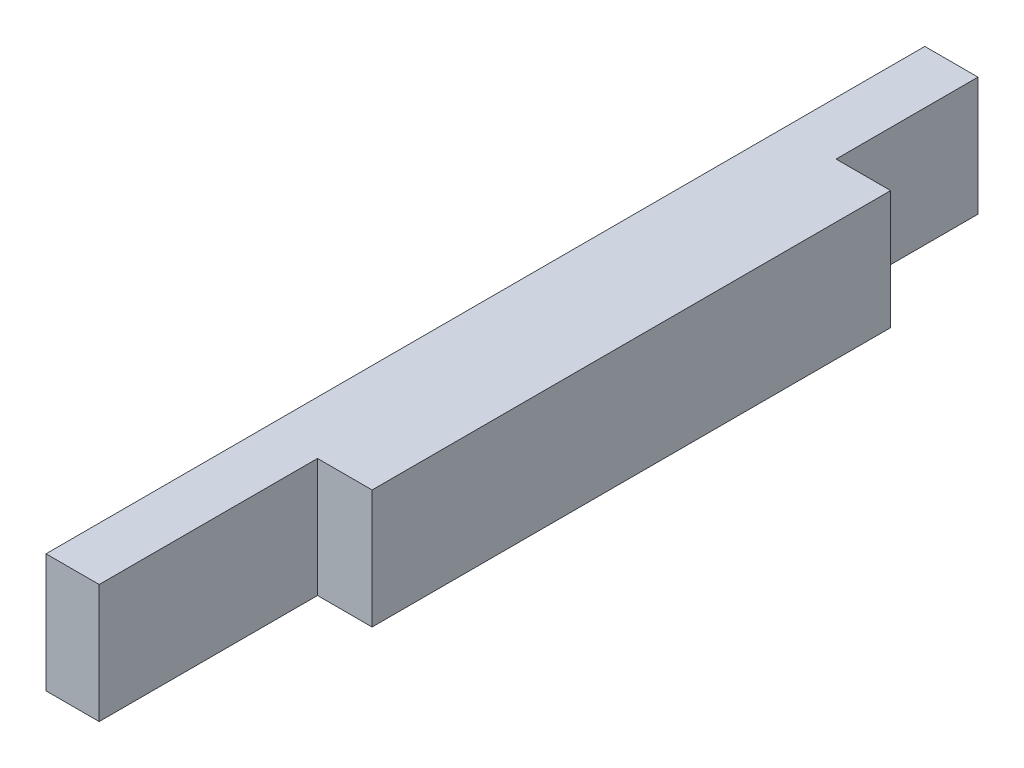
SolidWorks part; units mm, degrees
material "ABS"
ref_plane "Front Plane" through (0, 0, 0) normal (0, 0, 1) x (1, 0, 0)
ref_plane "Top Plane" through (0, 0, 0) normal (0, 1, 0) x (1, 0, 0)
ref_plane "Right Plane" through (0, 0, 0) normal (1, 0, 0) x (0, 0, -1)
sketch "Sketch2" plane through (0, 0, 0) normal (0, 1, 0) x (1, 0, 0)
  line L1 (0, 0) -> (4.95, 0)
  line L2 (0, 0) -> (0, 81.79)
  line L3 (0, 81.79) -> (4.95, 81.79)
  line L4 (10.03, 20.32) -> (10.03, 68.58)
  line L9 (10.03, 68.58) -> (4.95, 68.58)
  line L10 (4.95, 81.79) -> (4.95, 68.58)
  line L13 (10.03, 20.32) -> (4.95, 20.32)
  line L14 (4.95, 0) -> (4.95, 20.32)
  point P0 (0, 0)
  dimension "D1" = 81.79
  dimension "D2" = 48.26
  dimension "D3" = 20.32
  dimension "D4" = 4.95
  dimension "D5" = 10.03
  dimension "D6" = 4.95
extrude "Boss-Extrude1" add sketch "Sketch2" along normal blind 11.05
